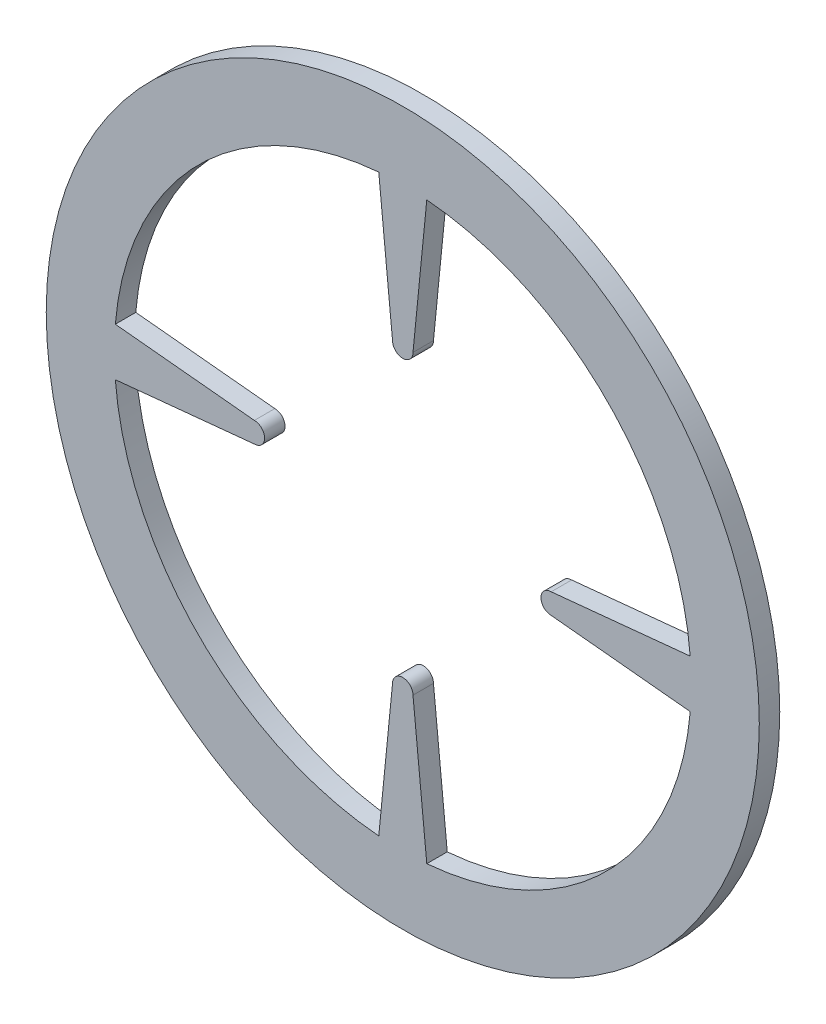
SolidWorks part; units mm, degrees
ref_plane "前基準面" through (0, 0, 0) normal (0, 0, 1) x (1, 0, 0)
ref_plane "上基準面" through (0, 0, 0) normal (0, 1, 0) x (1, 0, 0)
ref_plane "右基準面" through (0, 0, 0) normal (1, 0, 0) x (0, 0, -1)
sketch "草圖1" plane through (0, 0, 0) normal (0, 0, 1) x (1, 0, 0)
  line L0 (-0.03, 0.435) -> (-0.0704, 0.8425)
  line L1 (0, 0.435) -> (0, 0.8542) construction
  line L2 (0.03, 0.435) -> (0.0704, 0.8425)
  line L3 (0.435, 0.03) -> (0.8425, 0.0704)
  line L4 (0.435, -0.03) -> (0.8425, -0.0704)
  line L5 (0.03, -0.435) -> (0.0704, -0.8425)
  line L6 (-0.03, -0.435) -> (-0.0704, -0.8425)
  line L7 (-0.435, -0.03) -> (-0.8425, -0.0704)
  line L8 (-0.435, 0.03) -> (-0.8425, 0.0704)
  circle A0 centre (0, 0) radius 0.405
  arc A1 (0.0704, 0.8425) -> (-0.0704, 0.8425) centre (0, 0) ccw
  arc A2 (-0.03, 0.435) -> (0.03, 0.435) centre (0, 0.435) ccw
  arc A3 (0.8425, -0.0704) -> (0.8425, 0.0704) centre (0, 0) ccw
  arc A4 (0.435, 0.03) -> (0.435, -0.03) centre (0.435, 0) ccw
  arc A5 (-0.0704, -0.8425) -> (0.0704, -0.8425) centre (0, 0) ccw
  arc A6 (0.03, -0.435) -> (-0.03, -0.435) centre (0, -0.435) ccw
  arc A7 (-0.8425, 0.0704) -> (-0.8425, -0.0704) centre (0, 0) ccw
  arc A8 (-0.435, -0.03) -> (-0.435, 0.03) centre (-0.435, 0) ccw
  circle A9 centre (0, 0) radius 0.8455
  circle A10 centre (0, 0) radius 1.045
  point P27 (0, 0)
  dimension "D1" = 5.66
  dimension "D2" = 4
extrude "填料-伸長1" add sketch "草圖1" along normal blind 0.06
